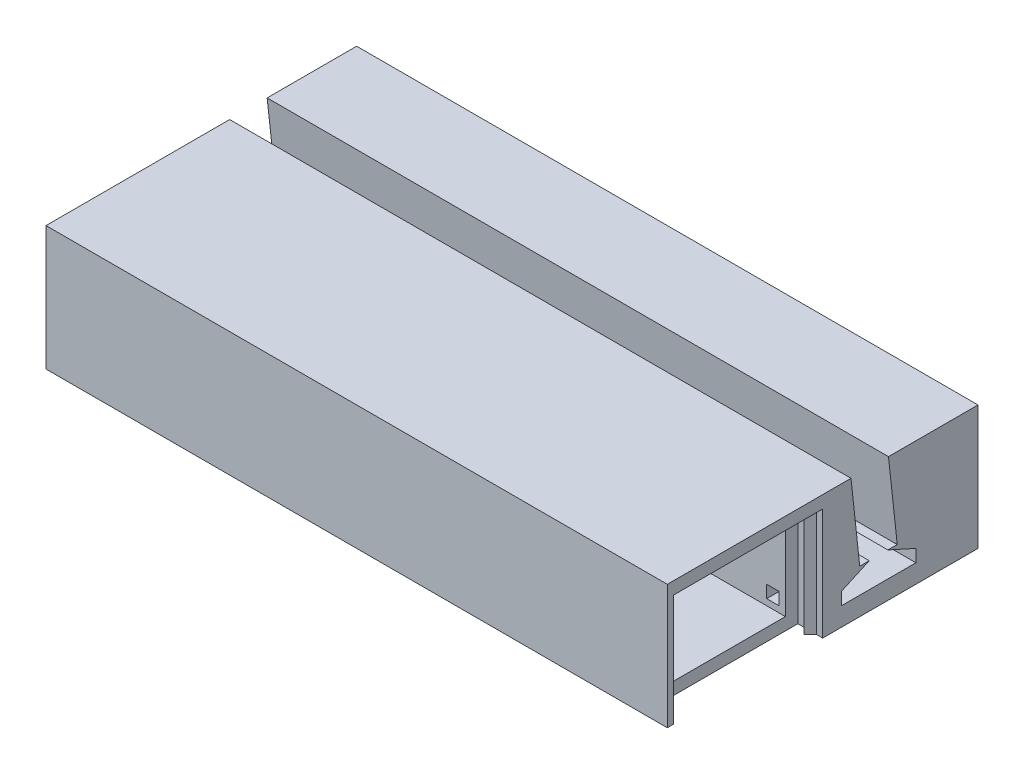
SolidWorks part; units mm, degrees
ref_plane "Přední rovina" through (0, 0, 0) normal (0, 0, 1) x (1, 0, 0)
ref_plane "Horní rovina" through (0, 0, 0) normal (0, 1, 0) x (1, 0, 0)
ref_plane "Pravá rovina" through (0, 0, 0) normal (1, 0, 0) x (0, 0, -1)
sketch "Skica2" plane through (0, 0, 0) normal (1, 0, 0) x (0, 0, -1)
  line L0 (4.5247, 10.31) -> (12, -2.961) construction
  line L1 (-25, 10) -> (25, 10)
  line L2 (-25, 10) -> (-25, -10)
  line L3 (-25, -10) -> (25, -10)
  line L4 (25, 10) -> (25, -10)
  line L5 (-25, 10) -> (25, -10) construction
  line L6 (-25, -10) -> (25, 10) construction
  line L7 (4.5247, 10.31) -> (10.4897, 10.9572)
  line L8 (4.5247, 10.31) -> (6.035, -3.6083)
  line L9 (6.035, -3.6083) -> (12, -2.961)
  line L10 (10.4897, 10.9572) -> (12, -2.961)
  line L16 (3, -7) -> (15, -7)
  line L17 (15, -7) -> (15, -4)
  line L33 (3, -4) -> (3, -7)
  line L34 (3, -7) -> (15, -4) construction
  line L35 (3, -4) -> (15, -7) construction
  line L36 (3, -4) -> (15, -4)
  line L46 (7.5, -2.961) -> (3, -5)
  line L47 (3, -5) -> (3, -2.961)
  line L48 (3, -2.961) -> (7.5, -2.961)
  line L49 (9, -4) -> (9, -7)
  line L50 (15, -5) -> (15, -2.961)
  line L51 (10.5, -2.961) -> (15, -5)
  line L52 (15, -2.961) -> (10.5, -2.961)
  line L54 (-11.965, -2.961) -> (-6, -2.961)
  line L56 (6.035, -3.6083) -> (12, -2.961)
  point P0 (0, 0)
  point P20 (8.2624, 3.6745)
  point P22 (0, 0)
  point P27 (9, -5.5)
  point P28 (0, 0)
  dimension "D1" = 50
  dimension "D2" = 20
  dimension "D3" = 14
  dimension "D4" = 6
  dimension "D5" = 12
  dimension "D6" = 3
  dimension "D7" = 4.5
  dimension "D8" = 3
  dimension "D9" = 2
  dimension "D10" = 3
  dimension "D11" = 16
  dimension "D12" = 3
  dimension "D14" = 4.039
extrude "Přidat vysunutím2" add sketch "Skica2" along normal blind 100 contours L52 L50 L17 L16 L33 L47 L48 L8 L1 L2 L3 L4 L10
sketch "Skica3" plane through (100, 0, 0) normal (1, 0, 0) x (0, 0, -1)
  line L0 (-25, 10) -> (-25, -10) construction
  line L1 (-22, 4) -> (-2, 4)
  line L2 (-22, 4) -> (-22, -8)
  line L3 (-22, -8) -> (-2, -8)
  line L4 (-2, 4) -> (-2, -8)
  line L7 (-25, 10) -> (4.5584, 10) construction
  dimension "D1" = 3
  dimension "D2" = 6
  dimension "D3" = 12
  dimension "D4" = 20
extrude "Odebrat vysunutím1" cut sketch "Skica3" against normal blind 98 from offset 1.2 offset against normal yes
sketch "Skica4" plane through (0, 0, 0) normal (-1, 0, 0) x (0, 0, 1)
  line L0 (5.6, -7) -> (5.6, -1.4)
  line L5 (5.6, -7) -> (19, -7)
  line L6 (19, -7) -> (19, -1.4)
  line L7 (5.6, -1.4) -> (19, -1.4)
  line L8 (25, 10) -> (25, -10) construction
  line L9 (25, -10) -> (-25, -10) construction
  point P0 (19, -4.2)
  dimension "D1" = 13.4
  dimension "D2" = 6
  dimension "D3" = 3
  dimension "D4" = 5.6
extrude "Odebrat vysunutím2" cut sketch "Skica4" against normal blind 95
sketch "Skica5" plane through (0, 0, -3) normal (0, 0, -1) x (-1, 0, 0)
  line L0 (-100, -7) -> (0, -7) construction
  line L1 (-93, -5) -> (-95, -5)
  line L2 (-93, -5) -> (-93, -7)
  line L3 (-93, -7) -> (-95, -7)
  line L4 (-95, -5) -> (-95, -7)
  line L6 (-100, 10) -> (-100, -10) construction
  dimension "D1" = 2
  dimension "D2" = 5
  dimension "D3" = 2
extrude "Odebrat vysunutím3" cut sketch "Skica5" against normal blind 9
sketch "Skica10" plane through (100, 0, 0) normal (1, 0, 0) x (0, 0, -1)
  line L0 (-25, 10) -> (-25, -10) construction
  line L1 (-25, 10) -> (4.5584, 10) construction
  line L2 (-22, 4) -> (-2, 4)
  arc A1 (-22, 4) -> (-2, 4) centre (-12, -8.49) cw
  dimension "D1" = 20
  dimension "D2" = 3
  dimension "D4" = 16
  dimension "D3" = 6
extrude "Odebrat vysunutím6" cut sketch "Skica10" against normal blind 98 from offset 1.2 offset against normal yes
sketch "Skica17" plane through (0, -10, 0) normal (0, -1, 0) x (1, 0, 0)
  line L0 (100, 25) -> (0, 25) construction
  line L1 (96, 24) -> (100, 24)
  line L2 (96, 24) -> (96, 0)
  line L3 (96, 0) -> (100, 0)
  line L4 (100, 24) -> (100, 0)
  line L5 (100, 25) -> (100, -25) construction
  line L6 (96, 24) -> (100, 0) construction
  line L7 (98, 0) -> (98, 24)
  line L8 (97, 24) -> (98, 23)
  line L9 (98, 23) -> (99, 24)
  line L10 (96, 12) -> (100, 12)
  line L11 (99, 24) -> (97, 24)
  line L12 (98, 1) -> (99, 0)
  line L13 (97, 0) -> (98, 1)
  line L14 (99, 0) -> (97, 0)
  point P11 (98, 12)
  point P15 (98, 12)
  line M11 (100, -25) -> (100, 25)
  dimension "D1" = 24
  dimension "D2" = 1
  dimension "D3" = 4
  dimension "D4" = 1
  dimension "D5" = 1
extrude "Odebrat vysunutím8" cut sketch "Skica17" against normal blind 18 contours L3 L13 L7 L10 L2 | L6 L7 L12 L3 | L10 L6 M11 | L7 L10 L4 L1 L9 | L6 L2 L10 | L1 L6 L7 L8
